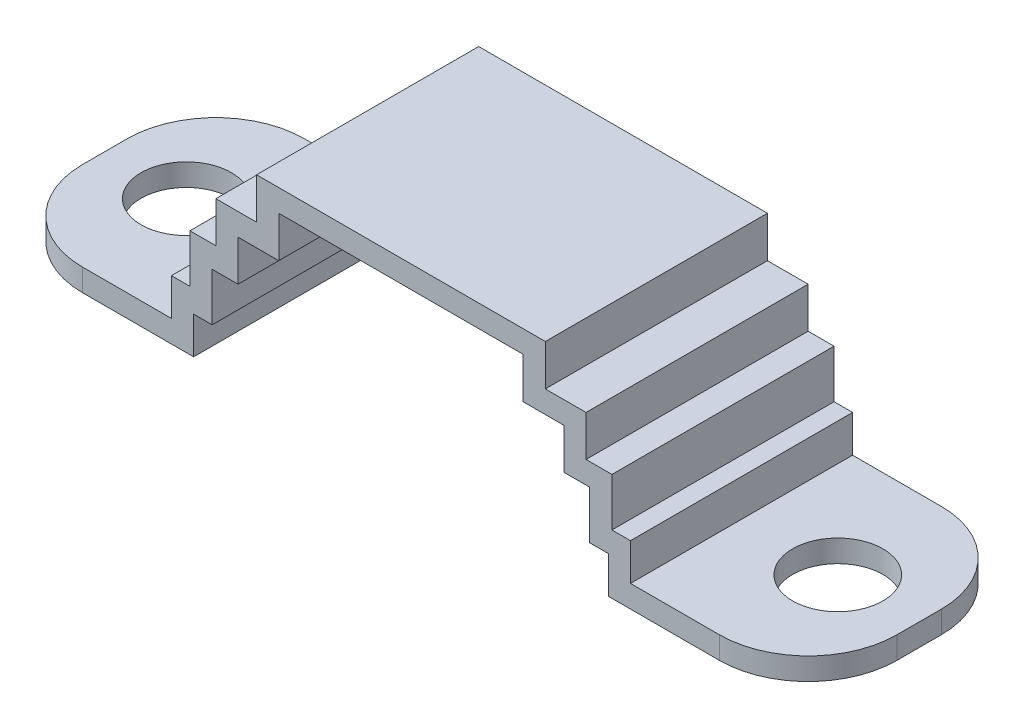
SolidWorks part; units mm, degrees
material "PBT General Purpose"
ref_plane "Front Plane" through (0, 0, 0) normal (0, 0, 1) x (1, 0, 0)
ref_plane "Top Plane" through (0, 0, 0) normal (0, 1, 0) x (1, 0, 0)
ref_plane "Right Plane" through (0, 0, 0) normal (1, 0, 0) x (0, 0, -1)
sketch "Sketch1" plane through (0, 0, 0) normal (0, 0, 1) x (1, 0, 0)
  line L0 (-55, 4.5) -> (-28, 4.5)
  line L1 (-28, 4.5) -> (-28, 9.5)
  line L2 (-28, 9.5) -> (-25.5, 9.5)
  line L3 (-25.5, 9.5) -> (-25.5, 16)
  line L4 (-25.5, 16) -> (-22, 16)
  line L5 (-22, 16) -> (-22, 21.5)
  line L6 (-22, 21.5) -> (-16.5, 21.5)
  line L7 (-16.5, 21.5) -> (-16.5, 27.05)
  line L8 (-16.5, 27.05) -> (0, 27.05)
  circle A0 centre (0, 0) radius 27.05
  dimension "D1" = 54.1
  dimension "D2" = 27
  dimension "D3" = 4.5
  dimension "D4" = 28
  dimension "D5" = 5
  dimension "D6" = 2.5
  dimension "D7" = 6.5
  dimension "D8" = 3.5
  dimension "D9" = 5.5
  dimension "D10" = 5.5
  dimension "D11" = 16.5
  dimension "D12" = 5.55
extrude "Extrude-Thin1" add sketch "Sketch1" along normal mid plane 30 thin contours L0 L1 L2 L3 L4 L5 L6 L7 L8
sketch "Sketch2" plane through (0, 7.5, 0) normal (0, 1, 0) x (1, 0, 0)
  line L0 (0, -15) -> (0, 15) construction
  circle A0 centre (-44, 0) radius 6.1
  dimension "D1" = 12.2
  dimension "D2" = 44
extrude "Cut-Extrude1" cut sketch "Sketch2" against normal through all
fillet "Fillet1" radius 12 2 edges at (-55, 6, -15) (-55, 6, 15)
mirror "Mirror1" about plane through (0, 30.05, 15) normal (1, 0, 0) of "Fillet1", "Cut-Extrude1", "Extrude-Thin1"
